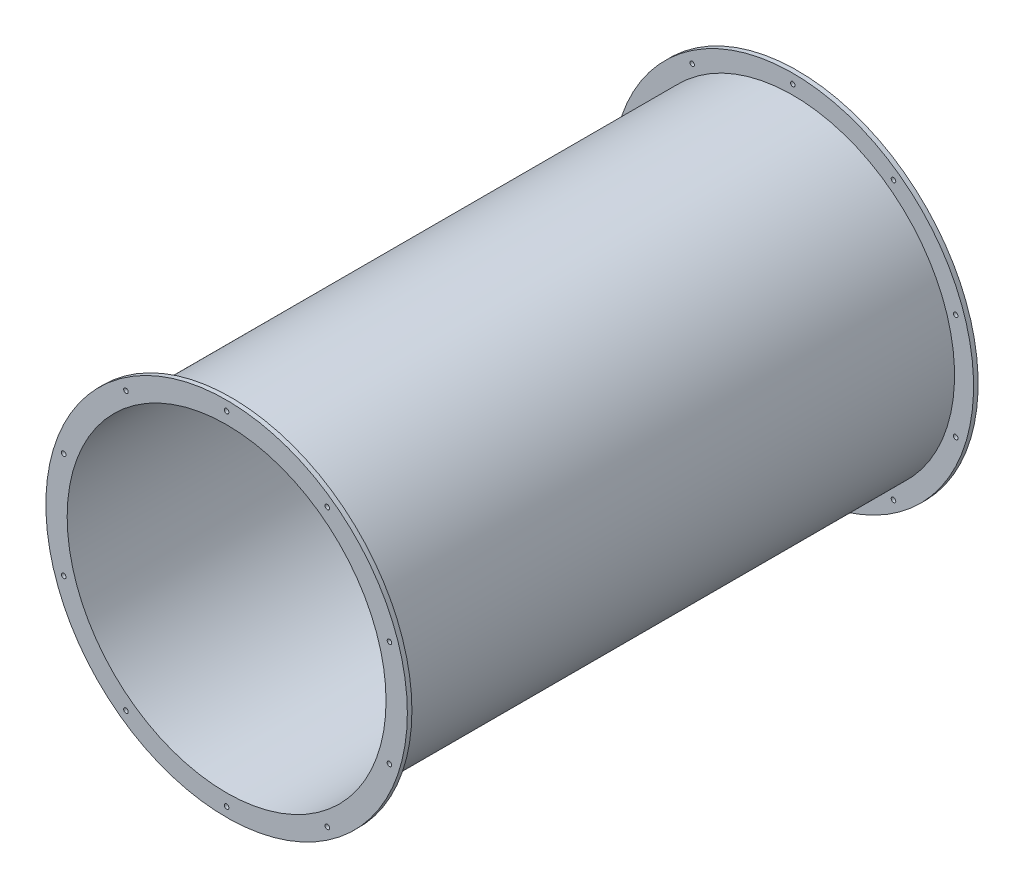
SolidWorks part; units mm, degrees
ref_plane "Front Plane" through (0, 0, 0) normal (0, 0, 1) x (1, 0, 0)
ref_plane "Top Plane" through (0, 0, 0) normal (0, 1, 0) x (1, 0, 0)
ref_plane "Right Plane" through (0, 0, 0) normal (1, 0, 0) x (0, 0, -1)
sketch "Sketch1" plane through (0, 0, 0) normal (0, 0, 1) x (1, 0, 0)
  circle A0 centre (0, 0) radius 425
  circle A1 centre (0, 0) radius 419
  dimension "D1" = 850
  dimension "D2" = 6
extrude "Boss-Extrude1" add sketch "Sketch1" along normal blind 1500
sketch "Sketch2" plane through (0, 0, 1500) normal (0, 0, 1) x (1, 0, 0)
  circle A0 centre (0, 0) radius 425
  circle A1 centre (0, 0) radius 425 construction
  circle A2 centre (0, 0) radius 475
  dimension "D1" = 950
extrude "Boss-Extrude2" add sketch "Sketch2" against normal blind 12
sketch "Sketch4" plane through (0, 0, 0) normal (0, 0, -1) x (-1, 0, 0)
  circle A0 centre (0, 0) radius 425
  circle A1 centre (0, 0) radius 425 construction
  circle A2 centre (0, 0) radius 475
  circle A3 centre (0, 0) radius 475 construction
extrude "Boss-Extrude3" add sketch "Sketch4" against normal blind 12
sketch "Sketch6" plane through (0, 0, 1500) normal (0, 0, 1) x (1, 0, 0)
  circle A0 centre (0, 0) radius 450 construction
  circle A1 centre (0, 450) radius 6
  circle A2 centre (264.5034, 364.0576) radius 6
  circle A3 centre (427.9754, 139.0576) radius 6
  circle A4 centre (427.9754, -139.0576) radius 6
  circle A5 centre (264.5034, -364.0576) radius 6
  circle A6 centre (0, -450) radius 6
  circle A7 centre (-264.5034, -364.0576) radius 6
  circle A8 centre (-427.9754, -139.0576) radius 6
  circle A9 centre (-427.9754, 139.0576) radius 6
  circle A10 centre (-264.5034, 364.0576) radius 6
  point P25 (0, 0)
  dimension "D1" = 900
  dimension "D2" = 12
extrude "Cut-Extrude3" cut sketch "Sketch6" against normal through all
equation "\"mbtOD\" = 850"
equation "\"mbtT\" = 6"
equation "\"mbtL\" = 1500"
equation "\"mbtFlangeOD\" = 950"
equation "\"mbtFlangeT\" = 12"
equation "\"mbtFlangeHoleDia\" = 12"
equation "\"D1@Boss-Extrude1\"=\"mbtL\""
equation "\"D1@Boss-Extrude2\"=\"mbtFlangeT\""
equation "\"D1@Boss-Extrude3\"=\"mbtFlangeT\""
equation "\"D1@Sketch1\"=\"mbtOD\""
equation "\"D2@Sketch1\"=\"mbtT\""
equation "\"D1@Sketch2\"=\"mbtFlangeOD\""
equation "\"D1@Sketch6\"=(\"mbtOD\"+\"mbtFlangeOD\")/2"
equation "\"D2@Sketch6\"=\"mbtFlangeHoleDia\""
equation "\"mbtOringSize\" = 10 "
equation "\"mbtOringDia\" = 620"
equation "\"mbtFlangeBoltCircleDia\" = 650"
equation "\"mbtWidth\" = 2250"
equation "\"skiWidth\" = 1250"
